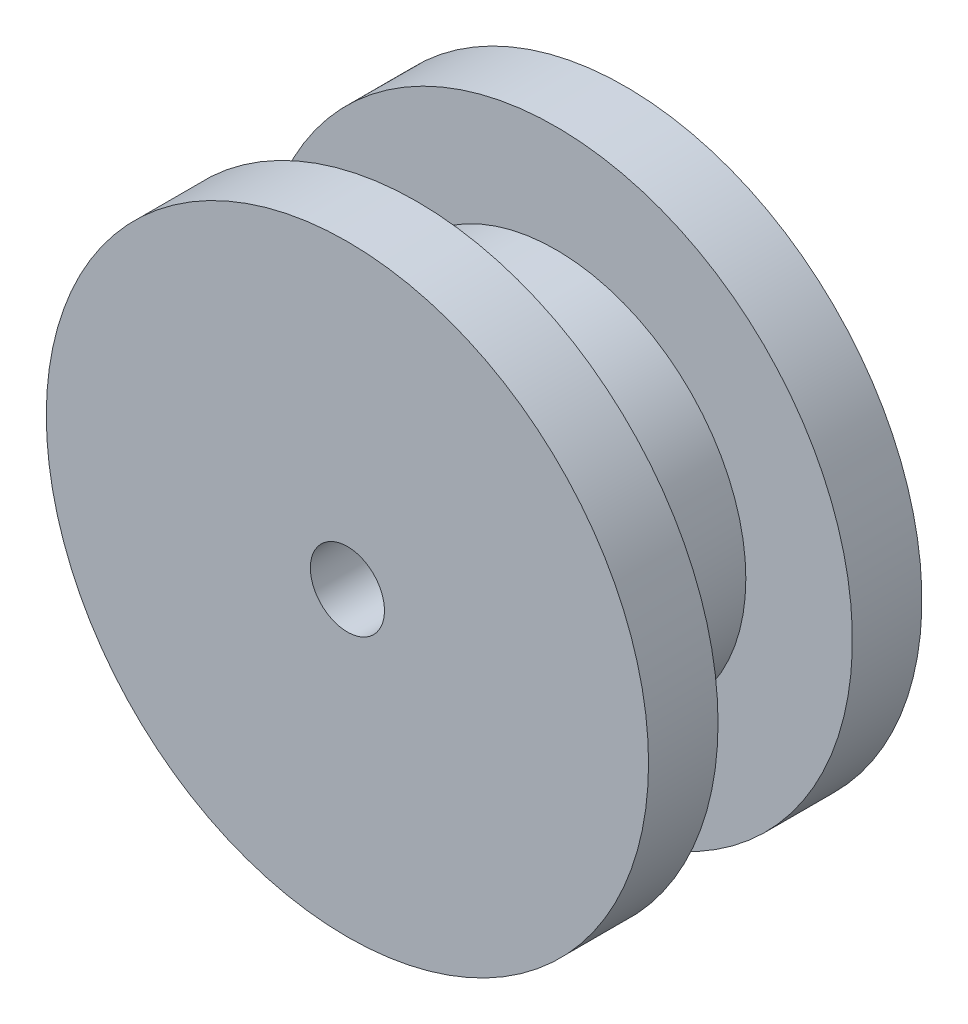
SolidWorks part; units mm, degrees
ref_plane "Front Plane" through (0, 0, 0) normal (0, 0, 1) x (1, 0, 0)
ref_plane "Top Plane" through (0, 0, 0) normal (0, 1, 0) x (1, 0, 0)
ref_plane "Right Plane" through (0, 0, 0) normal (1, 0, 0) x (0, 0, -1)
sketch "Sketch1" plane through (0, 0, 0) normal (0, 0, 1) x (1, 0, 0)
  circle A0 centre (0, 0) radius 20.5
  dimension "D1" = 41
extrude "Boss-Extrude1" add sketch "Sketch1" along normal blind 15
sketch "Sketch2" plane through (0, 0, 15) normal (0, 0, 1) x (1, 0, 0)
  circle A0 centre (0, 0) radius 32.5
  dimension "D1" = 65
extrude "Boss-Extrude2" add sketch "Sketch2" along normal blind 7.5
sketch "Sketch3" plane through (0, 0, 0) normal (0, 0, -1) x (-1, 0, 0)
  circle A0 centre (0, 0) radius 32
extrude "Boss-Extrude3" add sketch "Sketch3" along normal blind 7.5
sketch "Sketch4" plane through (0, 0, -7.5) normal (0, 0, -1) x (-1, 0, 0)
  circle A0 centre (0, 0) radius 4
extrude "Cut-Extrude1" cut sketch "Sketch4" against normal blind 30
